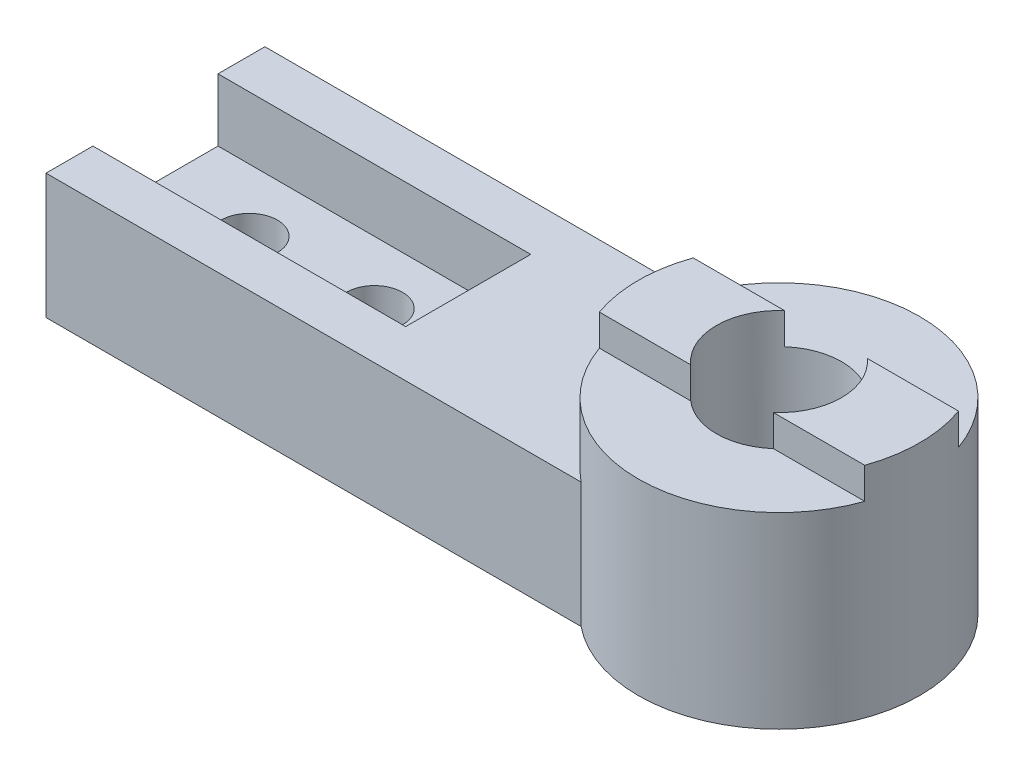
SolidWorks part; units mm, degrees
ref_plane "Ön Düzlem" through (0, 0, 0) normal (0, 0, 1) x (1, 0, 0)
ref_plane "Üst Düzlem" through (0, 0, 0) normal (0, 1, 0) x (1, 0, 0)
ref_plane "Sağ Düzlem" through (0, 0, 0) normal (1, 0, 0) x (0, 0, -1)
sketch "Çizim1" plane through (0, 0, 0) normal (0, 1, 0) x (1, 0, 0)
  circle A0 centre (0, 0) radius 22.5
  circle A1 centre (0, 0) radius 10
  dimension "D1" = 45
  dimension "D2" = 20
extrude "Yükseklik-Ekstrüzyon1" add sketch "Çizim1" along normal blind 30
sketch "Çizim2" plane through (0, 30, 0) normal (0, 1, 0) x (1, 0, 0)
  line L0 (-6.6144, 7.5) -> (-21.2132, 7.5)
  line L1 (21.2132, 7.5) -> (6.6144, 7.5)
  line L2 (21.2132, -7.5) -> (6.6144, -7.5)
  line L3 (-6.6144, -7.5) -> (-21.2132, -7.5)
  arc A0 (-21.2132, 7.5) -> (-21.2132, -7.5) centre (0, 0) ccw
  arc A1 (-6.6144, 7.5) -> (-6.6144, -7.5) centre (0, 0) ccw
  arc A2 (6.6144, -7.5) -> (6.6144, 7.5) centre (0, 0) ccw
  arc A3 (21.2132, -7.5) -> (21.2132, 7.5) centre (0, 0) ccw
extrude "Yükseklik-Ekstrüzyon2" add sketch "Çizim2" along normal blind 5
sketch "Çizim3" plane through (0, 0, 0) normal (0, 1, 0) x (1, 0, 0)
  line L0 (54.1097, 0) -> (-99.6832, 0) construction
  line L1 (-14.1421, -17.5) -> (-99.6832, -17.5)
  line L2 (-99.6832, 17.5) -> (-99.6832, -17.5)
  line L3 (-14.1421, 17.5) -> (-99.6832, 17.5)
  arc A1 (-21.2132, -7.5) -> (21.2132, -7.5) centre (0, 0) ccw construction
  arc A3 (-21.2132, -7.5) -> (-14.1421, -17.5) centre (0, 0) ccw
  arc A4 (-14.1421, 17.5) -> (-21.2132, 7.5) centre (0, 0) ccw
  arc A6 (-21.2132, 7.5) -> (-21.2132, -7.5) centre (0, 0) ccw construction
  arc A7 (-21.2132, 7.5) -> (-21.2132, -7.5) centre (0, 0) ccw
  point P3 (54.1097, 17.5)
  point P5 (54.1097, -17.5)
extrude "Yükseklik-Ekstrüzyon3" add sketch "Çizim3" along normal blind 20
sketch "Çizim4" plane through (0, 20, 0) normal (0, 1, 0) x (1, 0, 0)
  line L0 (-99.6832, 0) -> (60.6988, 0) construction
  line L1 (-99.6832, 17.5) -> (-99.6832, -17.5) construction
  line L2 (-99.6832, 10) -> (-49.6832, 10)
  line L3 (-49.6832, 10) -> (-49.6832, -10)
  line L4 (-49.6832, -10) -> (-99.6832, -10)
  line L5 (-99.6832, -10) -> (-99.6832, 10)
  dimension "D1" = 20
  dimension "D2" = 10
  dimension "D3" = 50
extrude "Kes-Ekstrüzyon1" cut sketch "Çizim4" against normal blind 10
sketch "Çizim5" plane through (0, 10, 0) normal (0, 1, 0) x (1, 0, 0)
  line L0 (-99.6832, 10) -> (-99.6832, -10) construction
  circle A0 centre (-84.6832, 0) radius 4.5
  circle A1 centre (-64.6832, 0) radius 4.5
  dimension "D1" = 9
  dimension "D2" = 15
  dimension "D3" = 20
extrude "Kes-Ekstrüzyon2" cut sketch "Çizim5" against normal blind 10
